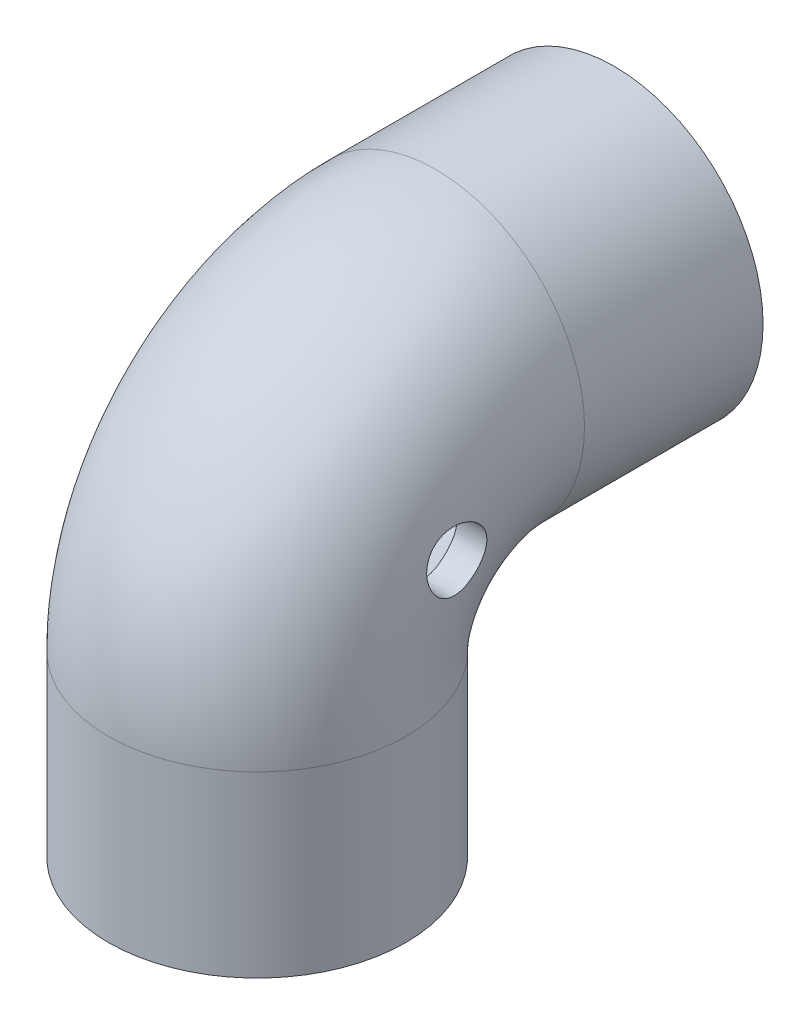
SolidWorks part; units mm, degrees
ref_plane "Plano frontal" through (0, 0, 0) normal (0, 0, 1) x (1, 0, 0)
ref_plane "Plano superior" through (0, 0, 0) normal (0, 1, 0) x (1, 0, 0)
ref_plane "Plano direito" through (0, 0, 0) normal (1, 0, 0) x (0, 0, -1)
sketch "Esboço3" plane through (0, 0, 0) normal (1, 0, 0) x (0, 0, -1)
  line L0 (0, 15) -> (0, 0)
  line L2 (15, 30) -> (30, 30)
  arc A0 (0, 15) -> (15, 30) centre (15, 15) cw
  point P5 (0, 30)
  dimension "D2" = 15
  dimension "D1" = 30
  dimension "D4" = 30
sketch "Esboço4" plane through (0, 0, 0) normal (0, 1, 0) x (1, 0, 0)
  circle A0 centre (0, 0) radius 12.5
  circle A1 centre (0, 0) radius 10
  dimension "D1" = 25
  dimension "D2" = 20
sweep "Varredura1" add profiles "Esboço4" path "Esboço3"
sketch "Esboço5" plane through (0, 0, 0) normal (1, 0, 0) x (0, 0, -1)
  line L0 (0, 15) -> (0, 42.5) construction
  line L1 (-12.5, 15) -> (12.5, 15) construction
  line L2 (0, 42.5) -> (15, 42.5) construction
  line L3 (15, 42.5) -> (15, 30) construction
  line L4 (15, 42.5) -> (15, 17.5) construction
  line L5 (15, 30) -> (0, 30) construction
  line L6 (13.2322, 16.7678) -> (-4.4454, 34.4454) construction
  arc A0 (15, 17.5) -> (12.5, 15) centre (15, 15) ccw construction
  arc A1 (15, 42.5) -> (-12.5, 15) centre (15, 15) ccw construction
  circle A2 centre (4.3934, 25.6066) radius 2.5
  dimension "D1" = 5
extrude "Corte-extrusão1" cut sketch "Esboço5" along normal blind 22 and the other way blind 23
